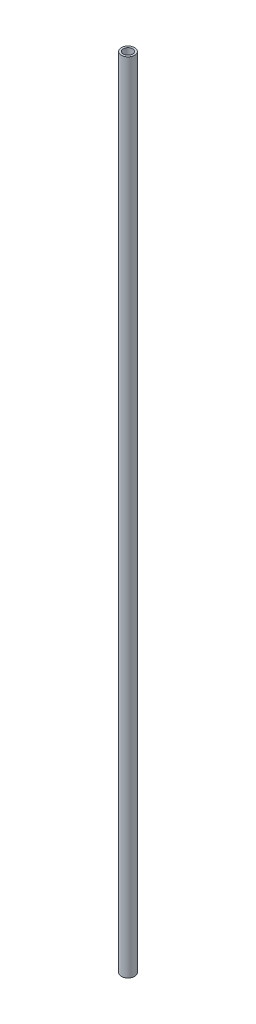
SolidWorks part; units mm, degrees
material "Thornel Mat VMA"
ref_plane "Front Plane" through (0, 0, 0) normal (0, 0, 1) x (1, 0, 0)
ref_plane "Top Plane" through (0, 0, 0) normal (0, 1, 0) x (1, 0, 0)
ref_plane "Right Plane" through (0, 0, 0) normal (1, 0, 0) x (0, 0, -1)
sketch "Sketch1" plane through (0, 0, 0) normal (0, 1, 0) x (1, 0, 0)
  circle A0 centre (0, 0) radius 5
  circle A1 centre (0, 0) radius 3.5
  dimension "D1" = 10
  dimension "D2" = 1.5
extrude "Boss-Extrude1" add sketch "Sketch1" along normal blind 600
